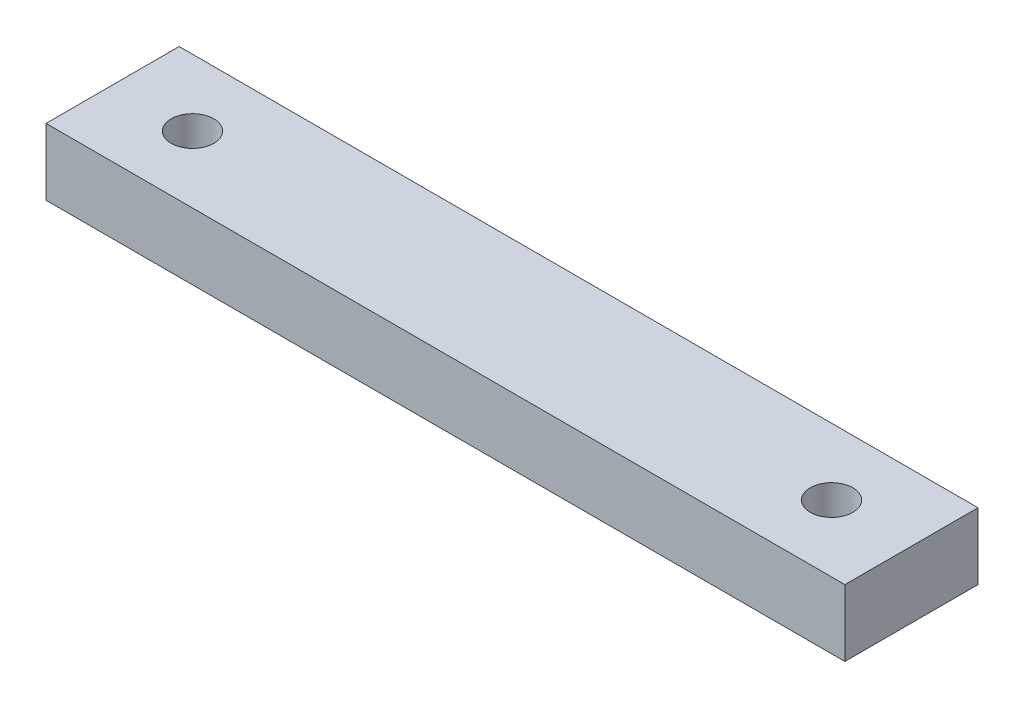
SolidWorks part; units mm, degrees
ref_plane "前视基准面" through (0, 0, 0) normal (0, 0, 1) x (1, 0, 0)
ref_plane "上视基准面" through (0, 0, 0) normal (0, 1, 0) x (1, 0, 0)
ref_plane "右视基准面" through (0, 0, 0) normal (1, 0, 0) x (0, 0, -1)
sketch "草图1" plane through (0, 0, 0) normal (0, 1, 0) x (1, 0, 0)
  line L0 (0, -55) -> (0, 55) construction
  line L1 (-30, -5) -> (30, -5)
  line L2 (-30, -5) -> (-30, 5)
  line L3 (-30, 5) -> (30, 5)
  line L4 (30, -5) -> (30, 5)
  line L5 (-30, -5) -> (30, 5) construction
  line L6 (-30, 5) -> (30, -5) construction
  circle A0 centre (-24, 0) radius 1.6
  circle A1 centre (24, 0) radius 1.6
  point P0 (0, 0)
  dimension "D2" = 48
  dimension "D4" = 3.2
  dimension "D1" = 60
  dimension "D3" = 10
extrude "凸台-拉伸1" add sketch "草图1" along normal blind 5
